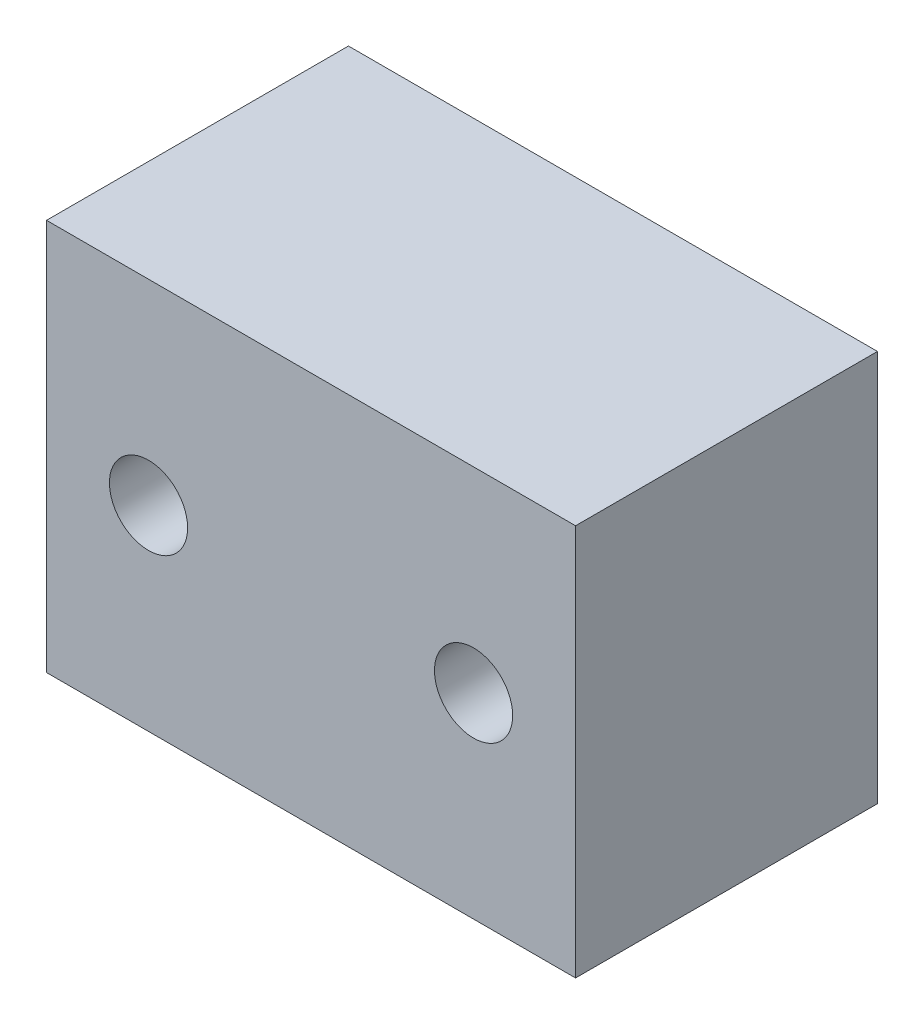
SolidWorks part; units mm, degrees
ref_plane "Ebene vorne" through (0, 0, 0) normal (0, 0, 1) x (1, 0, 0)
ref_plane "Ebene oben" through (0, 0, 0) normal (0, 1, 0) x (1, 0, 0)
ref_plane "Ebene rechts" through (0, 0, 0) normal (1, 0, 0) x (0, 0, -1)
sketch "Skizze1" plane through (0, 0, 0) normal (0, 0, 1) x (1, 0, 0)
  line L1 (77.8, -57.6) -> (-77.8, -57.6)
  line L2 (77.8, -57.6) -> (77.8, 57.6)
  line L3 (77.8, 57.6) -> (-77.8, 57.6)
  line L4 (-77.8, -57.6) -> (-77.8, 57.6)
  line L5 (77.8, -57.6) -> (-77.8, 57.6) construction
  line L6 (77.8, 57.6) -> (-77.8, -57.6) construction
  point P0 (0, 0)
  dimension "D1" = 115.2
  dimension "D2" = 155.6
extrude "Aufsatz-Linear austragen1" add sketch "Skizze1" along normal blind 88.8
hole_wizard "Stirnsenkung für M8 Senkschraube (Kopf Button)1" positions "Skizze4" profile "Skizze5" counterbore size "M8" standard "ANSI Metrisch" end condition through all
sketch "Skizze4" plane through (0, 0, 88.8) normal (0, 0, 1) x (1, 0, 0)
  line L0 (77.8, 57.6) -> (-77.8, 57.6) construction
  line L1 (-77.8, 57.6) -> (-77.8, -57.6) construction
  point P0 (-47.8, 0)
  dimension "D1" = 57.6
  dimension "D2" = 30
sketch "Skizze5" plane through (-47.8, 0, 88.8) normal (1, 0, 0) x (0, -1, 0)
  line L0 (0, 0) -> (0, 88.8)
  line L1 (0, 88.8) -> (4.5, 88.8)
  line L3 (4.5, 88.8) -> (4.5, 80)
  line L4 (4.5, 80) -> (11.5, 80)
  line L5 (11.5, 80) -> (11.5, 0)
  line L7 (11.5, 0) -> (0, 0)
  line L11 (0, -6.35) -> (0, 107.95) construction
  dimension "Bohrerdurchmesser" = 9
  dimension "Bohrungstiefe" = 88.8
  dimension "Senkdurchmesser2" = 23
  dimension "Senktiefe2" = 80
mirror "Spiegeln1" about plane through (0, 0, 0) normal (1, 0, 0) of "Stirnsenkung für M8 Senkschraube (Kopf Button)1"
